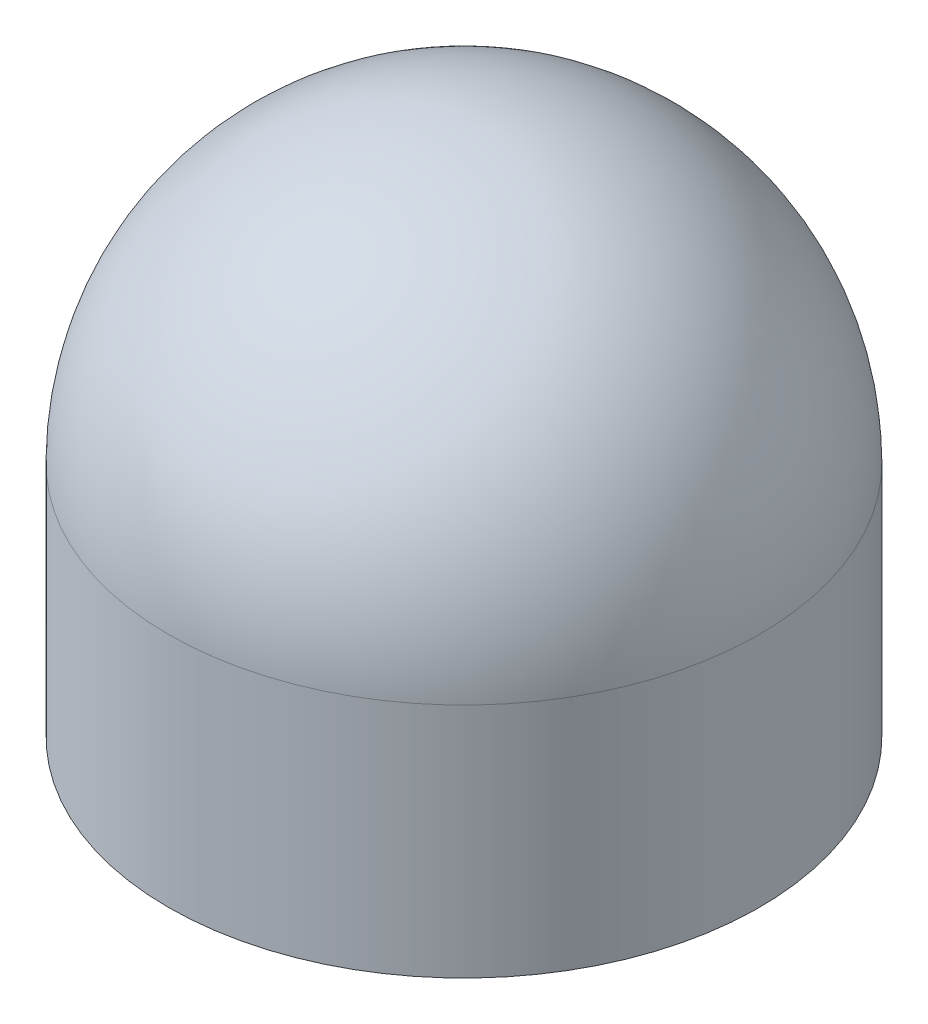
SolidWorks part; units mm, degrees
ref_plane "Front Plane" through (0, 0, 0) normal (0, 0, 1) x (1, 0, 0)
ref_plane "Top Plane" through (0, 0, 0) normal (0, 1, 0) x (1, 0, 0)
ref_plane "Right Plane" through (0, 0, 0) normal (1, 0, 0) x (0, 0, -1)
sketch "Sketch1" plane through (0, 0, 0) normal (0, 1, 0) x (1, 0, 0)
  circle A0 centre (0, 0) radius 25
extrude "Boss-Extrude1" add sketch "Sketch1" along normal blind 20
sketch "Sketch2" plane through (0, 20, 0) normal (0, 1, 0) x (1, 0, 0)
  line L0 (0, 25) -> (0, -25)
  arc A0 (0, -25) -> (0, 25) centre (0, 0) ccw
revolve "Revolve1" add sketch "Sketch2" angle 360 about L0
